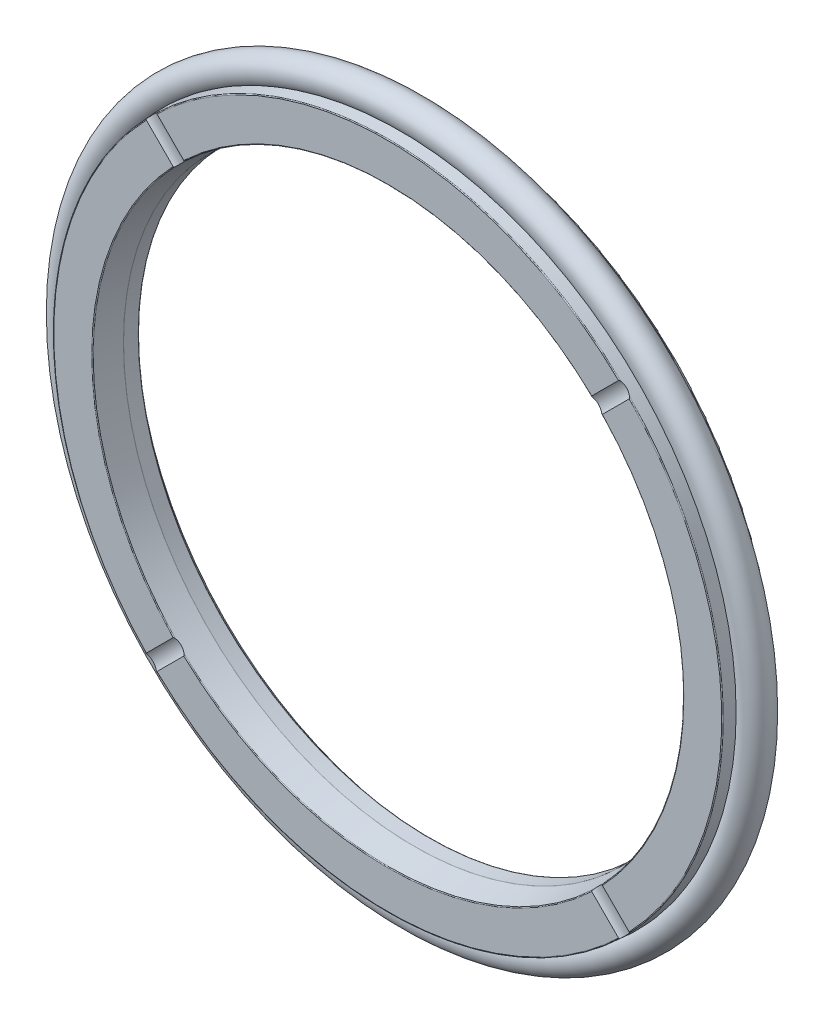
SolidWorks part; units mm, degrees
material "PTFE+FKM"
ref_plane "Front Plane" through (0, 0, 0) normal (0, 0, 1) x (1, 0, 0)
ref_plane "Top Plane" through (0, 0, 0) normal (0, 1, 0) x (1, 0, 0)
ref_plane "Right Plane" through (0, 0, 0) normal (1, 0, 0) x (0, 0, -1)
sketch "Sketch1" plane through (0, 0, 0) normal (1, 0, 0) x (0, 0, -1)
  line L0 (0, 35.9) -> (0, 40.275)
  line L1 (-0.2145, 40.4745) -> (-5.8073, 40.0668)
  line L2 (-5.9, 39.967) -> (-5.9, 35.4349)
  line L3 (-5.8162, 35.3362) -> (-2.708, 34.8263)
  line L4 (-2.6919, 34.825) -> (-0.9467, 34.825)
  line L5 (-0.87, 34.8608) -> (0, 35.9)
  line L6 (0, 0) -> (-16.4728, 0) construction
  arc A0 (-0.2145, 40.4745) -> (0, 40.275) centre (-0.2, 40.275) cw
  arc A1 (-0.9467, 34.825) -> (-0.87, 34.8608) centre (-0.9467, 34.925) ccw
  arc A2 (-2.708, 34.8263) -> (-2.6919, 34.825) centre (-2.6919, 34.925) ccw
  arc A3 (-5.9, 35.4349) -> (-5.8162, 35.3362) centre (-5.8, 35.4349) ccw
  arc A4 (-5.8073, 40.0668) -> (-5.9, 39.967) centre (-5.8, 39.967) ccw
  point P13 (-0.9, 34.825)
  point P16 (-2.7, 34.825)
  point P19 (-5.9, 35.35)
  point P22 (-5.9, 40.06)
  dimension "D2" = 0.2
  dimension "D4" = 80.95
  dimension "D10" = 0.1
  dimension "D1" = 5.9
  dimension "D3" = 80.12
  dimension "D5" = 69.65
  dimension "D6" = 71.8
  dimension "D7" = 0.9
  dimension "D8" = 3.2
  dimension "D9" = 70.7
revolve "Revolve1" add sketch "Sketch1" angle 360 about L6
sketch "Sketch2" plane through (0, 0, 0) normal (1, 0, 0) x (0, 0, -1)
  line L0 (0, 0) -> (14.1525, 0) construction
  line L1 (0, -40.275) -> (0, 40.275) construction
  line L2 (0, 0.9) -> (0, -0.9)
  arc A0 (0, 0.9) -> (0, -0.9) centre (1.495, 0) ccw
  dimension "D1" = 0.25
  dimension "D2" = 1.8
extrude "Cut-Extrude1" cut sketch "Sketch2" against normal through all and the other way through all
ref_axis "Axis1" through (0, 0, -19.1174) along (0, 0, 1)
pattern_circular "CirPattern1" count 4 over 360 about axis through (0, 0, -19.1174) along (0, 0, 1) of "Cut-Extrude1"
ref_plane "Plane1" through (0, 0, 0) normal (0.7071, -0.7071, 0) x (0.7071, 0.7071, 0)
sketch "Sketch3" plane through (0, 0, 0) normal (0.7071, -0.7071, 0) x (0.7071, 0.7071, 0)
  line L0 (0, 0) -> (0, 13.0703) construction
  line L1 (-0.9, 5.9) -> (0.9, 5.9)
  line L2 (39.967, 5.9) -> (-39.967, 5.9) construction
  arc A0 (-0.9, 5.9) -> (0.9, 5.9) centre (0, 7.395) ccw
  dimension "D1" = 0.25
  dimension "D2" = 1.8
extrude "Cut-Extrude2" cut sketch "Sketch3" against normal through all and the other way through all
pattern_circular "CirPattern2" count 4 over 360 about axis through (0, 0, -19.1174) along (0, 0, 1) of "Cut-Extrude2"
sketch "Sketch4" plane through (0, 0, 0) normal (1, 0, 0) x (0, 0, -1)
  line L0 (0, 0.9) -> (0, 40.2649) construction
  line L1 (0, 0) -> (-11.0861, 0) construction
  circle A0 centre (-3, 41.265) radius 1.765
  dimension "D1" = 3.53
  dimension "D2" = 3
  dimension "D3" = 79
revolve "Revolve2" add sketch "Sketch4" angle 360 about L1
